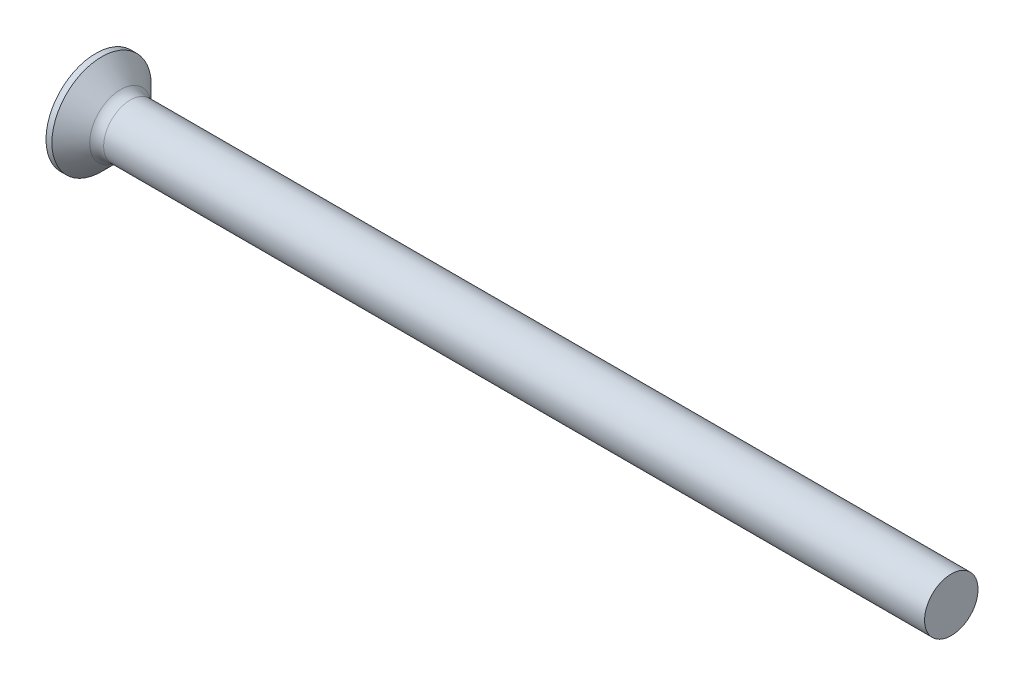
SolidWorks part; units mm, degrees
revolve "Base-Revolve" add sketch "BodySke" angle 360 about L5
sketch "BodySke" plane through (0, 0, 0) normal (0, 0, 1) x (1, 0, 0)
  line L0 (0, 0) -> (0, 4.65)
  line L1 (0, 4.65) -> (0.55, 4.65)
  line L2 (2.7, 2.5) -> (80, 2.5)
  line L3 (80, 2.5) -> (80, 0)
  line L4 (80, 0) -> (0, 0)
  line L5 (-6.35, 0) -> (82.55, 0) construction
  line L6 (2.7, -2.5) -> (80, -2.5) construction
  line L7 (0.55, -4.65) -> (2.7, -2.5) construction
  line L8 (0.55, 4.65) -> (2.7, 2.5)
  line L9 (0, -4.65) -> (0.55, -4.65) construction
  line L10 (3.5, 4.0875) -> (3.5, -5.4375) construction
  line L11 (12, 6.35) -> (12, -3.175) construction
  dimension "Diameter" = 5
  dimension "Length" = 80
  dimension "Head_ht" = 2.7
  dimension "Head_dia" = 9.3
  dimension "Head_ang" = 90
  dimension "D6" = 0.55
  dimension "Advance" = 0.8
  dimension "Thread_nom" = 68
cosmetic thread "ThreadCosmetic" [suppressed] parameters "Thread_length"=68, "Thread_minor"=4.11
ref_plane "Plane1" through (0, 0, 0) normal (0, 0, 1) x (1, 0, 0)
ref_plane "Plane2" through (0, 0, 0) normal (0, 1, 0) x (1, 0, 0)
ref_plane "Plane3" through (0, 0, 0) normal (1, 0, 0) x (0, 0, -1)
fillet "Fillet1" radius 1.3 1 edges at (2.7, 0, 2.5)
sketch "Sketch3" plane through (0, 0, 0) normal (-1, 0, 0) x (0, 0, 1)
  line L0 (-0.515, 2.45) -> (0.515, 2.45)
  line L1 (0.515, 2.45) -> (0.515, -2.45)
  line L2 (0.515, -2.45) -> (-0.515, -2.45)
  line L3 (-0.515, -2.45) -> (-0.515, 2.45)
  dimension "Cross_dia" = 4.9
  dimension "Cross_width" = 1.03
  dimension "D1" = 2.45
  dimension "D2" = 0.515
ref_plane "Plane4" through (3.05, 0, 0) normal (-1, 0, 0) x (0, 0, 1)
sketch "Sketch4" plane through (3.05, 0, 0) normal (-1, 0, 0) x (0, 0, 1)
  line L0 (-0.515, 0.9293) -> (0.515, 0.9293)
  line L3 (0.515, 0.9293) -> (0.515, -0.9293)
  line L4 (0.515, -0.9293) -> (-0.515, -0.9293)
  line L5 (-0.515, -0.9293) -> (-0.515, 0.9293)
  dimension "D2" = 1.8587
  dimension "D1" = 1.03
  dimension "D4" = 0.9293
  dimension "D3" = 0.515
loft "Recess" cut profiles "Sketch3", "Sketch4"
pattern_circular "RecPat" count 2 every 90 about axis through (0, 0, 0) along (1, 0, 0) of "Recess"
sketch "RecCorSke" plane through (0, 0, 0) normal (0, 0, 1) x (1, 0, 0)
  line L0 (-3.175, 0) -> (15.875, 0) construction
  line L2 (0, 0) -> (0, 1.0643)
  line L3 (0, 1.0643) -> (3.05, 0.851)
  line L4 (3.05, 0.851) -> (3.3265, 0)
  line L5 (3.3265, 0) -> (0, 0)
  dimension "Diameter" = 1.702
  dimension "Depth" = 3.05
  dimension "Draft_angle" = 4
  dimension "Bottom_angle" = 18
revolve "RecessCore" cut sketch "RecCorSke" angle 360 about L0
sketch "ThdSchSke" plane through (0, 0, 0) normal (0, 0, 1) x (1, 0, 0)
  line L0 (12, -2.055) -> (11.6884, -2.5)
  line L1 (12, -2.055) -> (12.3116, -2.5)
  line L2 (12.3116, -2.5) -> (12.3116, -3.125)
  line L3 (-3.175, 0) -> (5.1513, 0) construction
  line L5 (12.3116, -3.125) -> (11.6884, -3.125)
  line L6 (11.6884, -3.125) -> (11.6884, -2.5)
  line L7 (0, 4.65) -> (0, -4.65) construction
  dimension "Diameter" = 5
  dimension "Thread_minor" = 4.11
  dimension "Start" = 12
revolve "ThreadSchematic" [suppressed] cut sketch "ThdSchSke" angle 360 about L3
pattern_linear "ThdSchPat" [suppressed]
equation "\"D1@Sketch3\" = \"Cross_dia@Sketch3\" / 2"
equation "\"D2@Sketch3\" = \"Cross_width@Sketch3\" / 2"
equation "\"Depth@RecCorSke\" = \"Cross_depth@Plane4\""
equation "\"D1@Sketch4\" = \"Cross_width@Sketch3\""
equation "\"D2@Sketch4\" = \"Cross_dia@Sketch3\" - 2.0 * \"Cross_depth@Plane4\" * tan(26.5  * 0.017453292)"
equation "\"D3@Sketch4\" = \"D1@Sketch4\" / 2"
equation "\"D4@Sketch4\" = \"D2@Sketch4\" / 2"
equation "\"Thread_length@ThreadCosmetic\" = ((sgn( (\"Length@BodySke\" - \"Advance@BodySke\" * 1.0 - \"Head_ht@BodySke\" ) - \"Thread_nom@BodySke\" )-1)*( (\"Length@BodySke\" - \"Advance@BodySke\" * 1.0 - \"Head_ht@BodySke\" ) - \"Thread_nom@BodySke\" ))/-2+ \"Thread_nom@BodySke\""
equation "\"Thread_minor@ThdSchSke\" = \"Thread_minor@ThreadCosmetic\""
equation "\"Diameter@ThdSchSke\" = \"Diameter@BodySke\""
equation "\"Overcut@ThdSchSke\" = \"Diameter@BodySke\" * 1.25"
equation "\"Start@ThdSchSke\" = 0.000001 + \"Length@BodySke\" - \"Thread_length@ThreadCosmetic\"  '---Countersunk---"
equation "\"Num_threads@ThdSchPat\" = int( \"Thread_length@ThreadCosmetic\" / \"Advance@BodySke\" + 0.999 )  + 1"
equation "\"Advance@ThdSchPat\" = \"Thread_length@ThreadCosmetic\" /  (\"Num_threads@ThdSchPat\" - 1) 'relax it"
